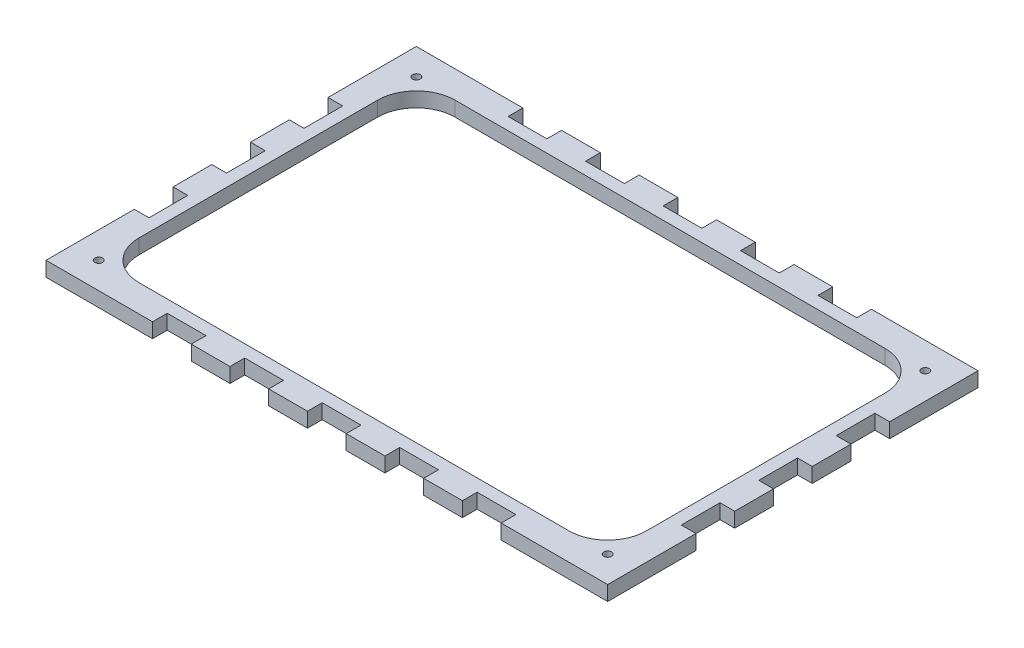
SolidWorks part; units mm, degrees
material "Maple"
ref_plane "Front Plane" through (0, 0, 0) normal (0, 0, 1) x (1, 0, 0)
ref_plane "Top Plane" through (0, 0, 0) normal (0, 1, 0) x (1, 0, 0)
ref_plane "Right Plane" through (0, 0, 0) normal (1, 0, 0) x (0, 0, -1)
sketch "Sketch1" plane through (0, 0, 0) normal (0, 1, 0) x (1, 0, 0)
  line L1 (0, 0) -> (145, 0)
  line L2 (0, 0) -> (0, -95.6)
  line L3 (0, -95.6) -> (145, -95.6)
  line L4 (145, 0) -> (145, -95.6)
  dimension "D1" = 145
  dimension "D2" = 95.6
extrude "Boss-Extrude1" add sketch "Sketch1" along normal blind 3.8
sketch "Sketch2" plane through (0, 3.8, 0) normal (0, 1, 0) x (1, 0, 0)
  line L0 (145, 0) -> (0, 0) construction
  line L1 (7, -7) -> (138, -7)
  line L2 (7, -7) -> (7, -88.6)
  line L3 (7, -88.6) -> (138, -88.6)
  line L4 (138, -7) -> (138, -88.6)
  line L5 (0, -95.6) -> (145, -95.6) construction
  line L6 (0, 0) -> (0, -95.6) construction
  line L7 (145, -95.6) -> (145, 0) construction
  dimension "D1" = 7
  dimension "D2" = 7
  dimension "D3" = 7
  dimension "D4" = 7
extrude "Cut-Extrude1" cut sketch "Sketch2" against normal through all
fillet "Fillet1" radius 10 4 edges at (138, 1.9, 88.6) (138, 1.9, 7) (7, 1.9, 7) (7, 1.9, 88.6)
sketch "Sketch3" plane through (0, 0, 0) normal (0, -1, 0) x (1, 0, 0)
  line L0 (145, 0) -> (0, 0) construction
  line L1 (0, 0) -> (0, 95.6) construction
  line L2 (0, 95.6) -> (145, 95.6) construction
  line L3 (145, 95.6) -> (145, 0) construction
  circle A0 centre (6.8, 88.8) radius 1
  circle A1 centre (138.2, 88.8) radius 1
  circle A2 centre (138.2, 6.8) radius 1
  circle A3 centre (6.8, 6.8) radius 1
  dimension "D1" = 2
  dimension "D2" = 2
  dimension "D3" = 2
  dimension "D4" = 2
  dimension "D5" = 6.8
  dimension "D6" = 6.8
  dimension "D7" = 6.8
  dimension "D8" = 6.8
  dimension "D9" = 6.8
  dimension "D10" = 6.8
  dimension "D11" = 6.8
  dimension "D12" = 6.8
extrude "Cut-Extrude2" cut sketch "Sketch3" against normal through all
sketch "Sketch8" plane through (0, 0, 0) normal (0, -1, 0) x (-1, 0, 0)
  line L0 (-72.5, -95.6) -> (-72.5, 0) construction
  line L1 (0, -95.6) -> (-145, -95.6) construction
  line L2 (-145, 0) -> (0, 0) construction
  line L4 (-67.5, -95.6) -> (-77.5, -95.6)
  line L5 (-67.5, -95.6) -> (-67.5, -91.8)
  line L6 (-67.5, -91.8) -> (-77.5, -91.8)
  line L7 (-77.5, -95.6) -> (-77.5, -91.8)
  line L8 (-67.5, -95.6) -> (-77.5, -91.8) construction
  line L9 (-67.5, -91.8) -> (-77.5, -95.6) construction
  line L10 (-67.5, -3.8) -> (-77.5, -3.8)
  line L11 (-67.5, -3.8) -> (-67.5, 0)
  line L12 (-67.5, 0) -> (-77.5, 0)
  line L13 (-77.5, -3.8) -> (-77.5, 0)
  line L14 (-67.5, -3.8) -> (-77.5, 0) construction
  line L15 (-67.5, 0) -> (-77.5, -3.8) construction
  point P6 (-72.5, -93.7)
  point P11 (-72.5, -1.9)
  dimension "D1" = 3.8
  dimension "D2" = 10
extrude "Cut-Extrude5" cut sketch "Sketch8" against normal through all
pattern_linear "LPattern3" count 4 spacing 20 along (1, 0, 0) count 4 spacing 20 along (-1, 0, 0) of "Cut-Extrude5"
sketch "Sketch9" plane through (0, 0, 0) normal (0, -1, 0) x (-1, 0, 0)
  line L0 (0, -47.8) -> (-145, -47.8) construction
  line L1 (0, 0) -> (0, -95.6) construction
  line L2 (-145, -95.6) -> (-145, 0) construction
  line L4 (0, -52.8) -> (-3.8, -52.8)
  line L5 (0, -52.8) -> (0, -42.8)
  line L6 (0, -42.8) -> (-3.8, -42.8)
  line L7 (-3.8, -52.8) -> (-3.8, -42.8)
  line L8 (0, -52.8) -> (-3.8, -42.8) construction
  line L9 (0, -42.8) -> (-3.8, -52.8) construction
  line L10 (-141.2, -52.8) -> (-145, -52.8)
  line L11 (-141.2, -52.8) -> (-141.2, -42.8)
  line L12 (-141.2, -42.8) -> (-145, -42.8)
  line L13 (-145, -52.8) -> (-145, -42.8)
  line L14 (-141.2, -52.8) -> (-145, -42.8) construction
  line L15 (-141.2, -42.8) -> (-145, -52.8) construction
  point P6 (-1.9, -47.8)
  point P11 (-143.1, -47.8)
  dimension "D1" = 3.8
  dimension "D2" = 10
extrude "Cut-Extrude6" cut sketch "Sketch9" against normal through all
pattern_linear "LPattern4" count 3 spacing 20 along (0, 0, 1) count 3 spacing 20 along (0, 0, -1) of "Cut-Extrude6"
sketch "Sketch11" plane through (0, 0, 0) normal (0, -1, 0) x (-1, 0, 0)
  line L1 (-145, -82.8) -> (-141.2, -82.8)
  line L2 (-145, -82.8) -> (-145, -92.8)
  line L3 (-145, -92.8) -> (-141.2, -92.8)
  line L4 (-141.2, -82.8) -> (-141.2, -92.8)
  line L5 (-127.5, -95.6) -> (-137.5, -95.6)
  line L6 (-127.5, -95.6) -> (-127.5, -91.8)
  line L7 (-127.5, -91.8) -> (-137.5, -91.8)
  line L8 (-137.5, -95.6) -> (-137.5, -91.8)
  line L9 (-127.5, 0) -> (-137.5, 0)
  line L10 (-127.5, 0) -> (-127.5, -3.8)
  line L11 (-127.5, -3.8) -> (-137.5, -3.8)
  line L12 (-137.5, 0) -> (-137.5, -3.8)
  line L13 (-145, -12.8) -> (-141.2, -12.8)
  line L14 (-145, -12.8) -> (-145, -2.8)
  line L15 (-145, -2.8) -> (-141.2, -2.8)
  line L16 (-141.2, -12.8) -> (-141.2, -2.8)
  line L17 (0, -12.8) -> (-3.8, -12.8)
  line L18 (0, -12.8) -> (0, -2.8)
  line L19 (0, -2.8) -> (-3.8, -2.8)
  line L20 (-3.8, -12.8) -> (-3.8, -2.8)
  line L21 (-17.5, -3.8) -> (-7.5, -3.8)
  line L22 (-17.5, -3.8) -> (-17.5, 0)
  line L23 (-17.5, 0) -> (-7.5, 0)
  line L24 (-7.5, -3.8) -> (-7.5, 0)
  line L25 (0, -92.8) -> (-3.8, -92.8)
  line L26 (0, -92.8) -> (0, -82.8)
  line L27 (0, -82.8) -> (-3.8, -82.8)
  line L28 (-3.8, -92.8) -> (-3.8, -82.8)
  line L29 (-17.5, -95.6) -> (-7.5, -95.6)
  line L30 (-17.5, -95.6) -> (-17.5, -91.8)
  line L31 (-17.5, -91.8) -> (-7.5, -91.8)
  line L32 (-7.5, -95.6) -> (-7.5, -91.8)
extrude "Boss-Extrude4" add sketch "Sketch11" against normal through all
equation "\"D2@Sketch2\"=\"D1@Sketch2\""
equation "\"D3@Sketch2\"=\"D1@Sketch2\""
equation "\"D4@Sketch2\"=\"D1@Sketch2\""
equation "\"D2@Sketch3\"=\"D1@Sketch3\""
equation "\"D3@Sketch3\"=\"D1@Sketch3\""
equation "\"D4@Sketch3\"=\"D1@Sketch3\""
equation "\"D7@Sketch3\"=\"D6@Sketch3\""
equation "\"D8@Sketch3\"=\"D7@Sketch3\""
equation "\"D9@Sketch3\"=\"D5@Sketch3\""
equation "\"D10@Sketch3\"=\"D6@Sketch3\""
equation "\"D11@Sketch3\"=\"D7@Sketch3\""
equation "\"D12@Sketch3\"=\"D8@Sketch3\""
